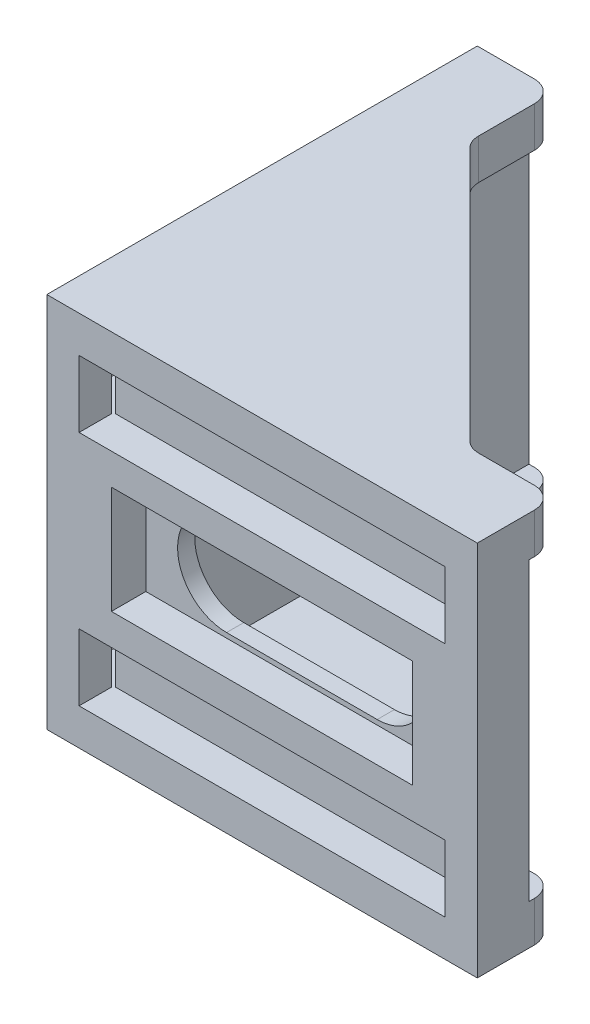
SolidWorks part; units mm, degrees
ref_plane "Спереди" through (0, 0, 0) normal (0, 0, 1) x (1, 0, 0)
ref_plane "Сверху" through (0, 0, 0) normal (0, 1, 0) x (1, 0, 0)
ref_plane "Справа" through (0, 0, 0) normal (1, 0, 0) x (0, 0, -1)
sketch "Эскиз1" plane through (0, 0, 0) normal (0, 1, 0) x (1, 0, 0)
  line L0 (0, 22.4475) -> (0, -16.6075) construction
  line L1 (-30.4775, 0) -> (51.9746, 0) construction
  line L6 (0, 40) -> (0, 0)
  line L7 (0, 0) -> (40, 0)
  line L8 (0, 40) -> (5.3, 40)
  line L9 (7.3, 38) -> (7.3, 32)
  line L10 (40, 0) -> (40, 5.3)
  line L11 (38, 7.3) -> (32, 7.3)
  line L12 (32, 7.3) -> (7.3, 32)
  arc A0 (7.3, 38) -> (5.3, 40) centre (5.3, 38) ccw
  arc A1 (40, 5.3) -> (38, 7.3) centre (38, 5.3) ccw
  point P14 (7.3, 40)
  dimension "D4" = 2
  dimension "D5" = 2
  dimension "D1" = 40
  dimension "D2" = 7.3
  dimension "D3" = 8
extrude "Бобышка-Вытянуть1" add sketch "Эскиз1" along normal mid plane 35
sketch "Эскиз2" plane through (0, 0, -40) normal (0, 0, -1) x (-1, 0, 0)
  line L1 (-40, 13.75) -> (-4.8, 13.75)
  line L2 (-40, 13.75) -> (-40, -13.75)
  line L3 (-40, -13.75) -> (-4.8, -13.75)
  line L4 (-4.8, 13.75) -> (-4.8, -13.75)
  line L5 (-40, 13.75) -> (-4.8, -13.75) construction
  line L6 (-40, -13.75) -> (-4.8, 13.75) construction
  line L7 (5.5905, 0) -> (-50.0874, 0) construction
  line L9 (-5.3, 17.5) -> (0, 17.5) construction
  line L10 (-5.3, -17.5) -> (0, -17.5) construction
  line L11 (-40, 17.5) -> (-40, -17.5) construction
  line L12 (0, 17.5) -> (0, -17.5) construction
  point P0 (-22.4, 0)
  dimension "D1" = 27.5
  dimension "D2" = 4.8
extrude "Вырез-Вытянуть1" cut sketch "Эскиз2" against normal blind 35.2
sketch "Эскиз3" plane through (0, 0, 0) normal (0, 0, 1) x (1, 0, 0)
  line L0 (-4.893, 0) -> (36.0529, 0) construction
  line L1 (13.5, 0) -> (27.5, 0) construction
  line L2 (13.5, 4.55) -> (27.5, 4.55)
  line L3 (13.5, -4.55) -> (27.5, -4.55)
  line L4 (20.5, 6.4843) -> (20.5, -4.55) construction
  line L8 (0, 17.5) -> (0, -17.5) construction
  arc A0 (13.5, 4.55) -> (13.5, -4.55) centre (13.5, 0) ccw
  arc A1 (27.5, -4.55) -> (27.5, 4.55) centre (27.5, 0) ccw
  point P5 (20.5, 0)
  dimension "D1" = 9.1
  dimension "D2" = 23.1
  dimension "D3" = 20.5
extrude "Вырез-Вытянуть2" cut sketch "Эскиз3" against normal through all
sketch "Эскиз4" plane through (0, 0, 0) normal (-1, 0, 0) x (0, 0, 1)
  line L0 (4.893, 0) -> (-43.873, 0) construction
  line L1 (-27.5, 0) -> (-13.5, 0) construction
  line L2 (-27.5, 4.55) -> (-13.5, 4.55)
  line L3 (-27.5, -4.55) -> (-13.5, -4.55)
  line L4 (0, 17.5) -> (0, -17.5) construction
  arc A0 (-27.5, 4.55) -> (-27.5, -4.55) centre (-27.5, 0) ccw
  arc A1 (-13.5, -4.55) -> (-13.5, 4.55) centre (-13.5, 0) ccw
  point P5 (-20.5, 0)
  dimension "D3" = 23.1
  dimension "D1" = 9.1
  dimension "D2" = 20.5
extrude "Вырез-Вытянуть3" cut sketch "Эскиз4" against normal through all
sketch "Эскиз5" plane through (0, 0, 0) normal (-1, 0, 0) x (0, 0, 1)
  line L0 (0, 0) -> (-40, 0) construction
  line L1 (0, 17.5) -> (0, -17.5) construction
  line L2 (-40, 17.5) -> (-40, -17.5) construction
  line L3 (-20, 21.3607) -> (-20, -20.6053) construction
  line L4 (-37, 14.1) -> (-3, 14.1)
  line L5 (-37, 14.1) -> (-37, 7.9)
  line L6 (-37, 7.9) -> (-3, 7.9)
  line L7 (-3, 14.1) -> (-3, 7.9)
  line L8 (-37, 14.1) -> (-3, 7.9) construction
  line L9 (-37, 7.9) -> (-3, 14.1) construction
  line L10 (-40, 17.5) -> (0, 17.5) construction
  line L11 (-37, -7.9) -> (-3, -14.1) construction
  line L12 (-37, -14.1) -> (-3, -7.9) construction
  line L13 (-20, -21.3607) -> (-20, 20.6053) construction
  line L14 (-3, -14.1) -> (-3, -7.9)
  line L15 (-37, -7.9) -> (-3, -7.9)
  line L16 (-37, -14.1) -> (-37, -7.9)
  line L17 (-37, -14.1) -> (-3, -14.1)
  line L19 (-34, 5) -> (-6, 5)
  line L20 (-34, 5) -> (-34, -5)
  line L21 (-34, -5) -> (-6, -5)
  line L22 (-6, 5) -> (-6, -5)
  line L23 (-34, 5) -> (-6, -5) construction
  line L24 (-34, -5) -> (-6, 5) construction
  point P6 (-20, 11)
  point P21 (-20, -11)
  point P22 (-20, 0)
  dimension "D1" = 6.2
  dimension "D2" = 34
  dimension "D3" = 3.4
  dimension "D4" = 28
  dimension "D5" = 10
extrude "Вырез-Вытянуть4" cut sketch "Эскиз5" against normal blind 3.2
sketch "Эскиз6" plane through (0, 0, 0) normal (0, 0, 1) x (1, 0, 0)
  line L0 (0, 0) -> (40, 0) construction
  line L1 (0, 17.5) -> (0, -17.5) construction
  line L2 (40, 17.5) -> (40, -17.5) construction
  line L3 (20, 16.1925) -> (20, -14.8397) construction
  line L4 (3, 14.1) -> (37, 14.1)
  line L5 (3, 14.1) -> (3, 7.9)
  line L6 (3, 7.9) -> (37, 7.9)
  line L7 (37, 14.1) -> (37, 7.9)
  line L8 (3, 14.1) -> (37, 7.9) construction
  line L9 (3, 7.9) -> (37, 14.1) construction
  line L10 (0, 17.5) -> (40, 17.5) construction
  line L11 (3, -7.9) -> (37, -14.1) construction
  line L12 (3, -14.1) -> (37, -7.9) construction
  line L13 (37, -14.1) -> (37, -7.9)
  line L14 (3, -7.9) -> (37, -7.9)
  line L15 (3, -14.1) -> (3, -7.9)
  line L16 (3, -14.1) -> (37, -14.1)
  line L18 (6, 5) -> (34, 5)
  line L19 (6, 5) -> (6, -5)
  line L20 (6, -5) -> (34, -5)
  line L21 (34, 5) -> (34, -5)
  line L22 (6, 5) -> (34, -5) construction
  line L23 (6, -5) -> (34, 5) construction
  point P6 (20, 11)
  point P20 (20, -11)
  point P21 (20, 0)
  dimension "D1" = 34
  dimension "D2" = 6.2
  dimension "D3" = 3.4
  dimension "D4" = 10
  dimension "D5" = 28
extrude "Вырез-Вытянуть5" cut sketch "Эскиз6" against normal blind 3.2
fillet "Скругление1" radius 2 4 edges at (32, -15.625, -7.3) (7.3, -15.625, -32) (32, 15.625, -7.3) (7.3, 15.625, -32)
